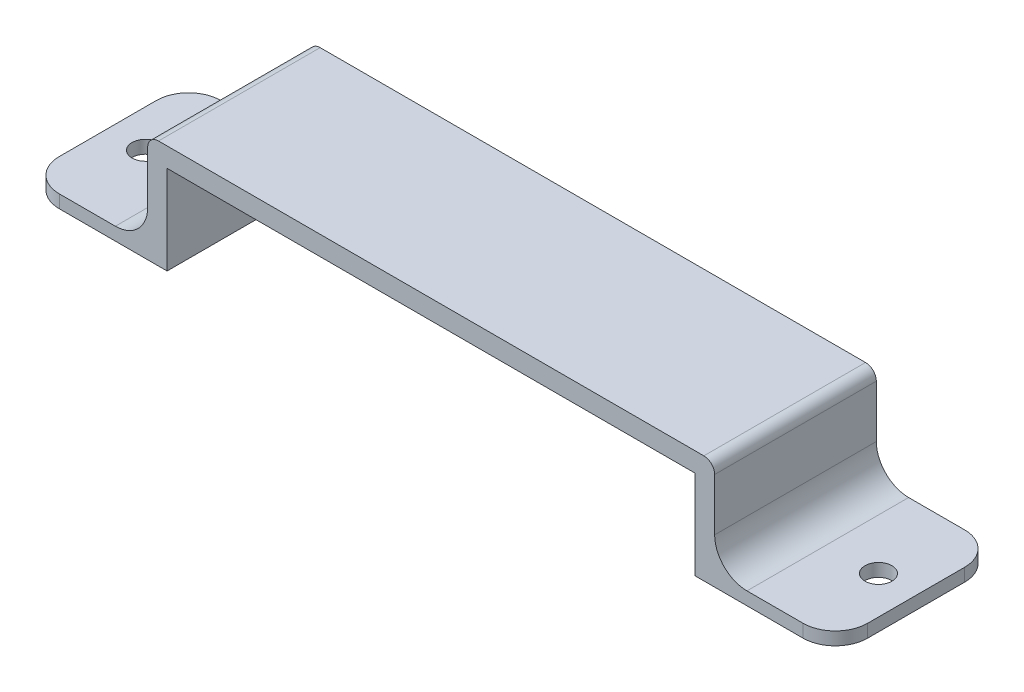
SolidWorks part; units mm, degrees
ref_plane "Front Plane" through (0, 0, 0) normal (0, 0, 1) x (1, 0, 0)
ref_plane "Top Plane" through (0, 0, 0) normal (0, 1, 0) x (1, 0, 0)
ref_plane "Right Plane" through (0, 0, 0) normal (1, 0, 0) x (0, 0, -1)
sketch "Sketch1" plane through (0, 0, 0) normal (0, 0, 1) x (1, 0, 0)
  line L0 (-21.8742, 0) -> (-8.8742, 0)
  line L1 (-8.8742, 0) -> (-8.8742, 8.25)
  line L2 (-8.8742, 8.25) -> (40.1258, 8.25)
  line L3 (40.1258, 8.25) -> (40.1258, 0)
  line L4 (40.1258, 0) -> (53.1258, 0)
  line L5 (53.1258, 0) -> (53.1258, 1.2)
  line L6 (53.1258, 1.2) -> (41.9258, 1.2)
  line L7 (41.9258, 1.2) -> (41.9258, 10.05)
  line L8 (41.9258, 10.05) -> (-10.6742, 10.05)
  line L9 (-10.6742, 10.05) -> (-10.6742, 1.2)
  line L10 (-10.6742, 1.2) -> (-21.8742, 1.2)
  line L11 (-21.8742, 1.2) -> (-21.8742, 0)
  point P12 (53.1258, 0.6)
  dimension "D1" = 1.2
  dimension "D2" = 75
  dimension "D3" = 49
  dimension "D4" = 1.8
  dimension "D5" = 8.25
  dimension "D6" = 1.8
extrude "Boss-Extrude1" add sketch "Sketch1" along normal blind 15
sketch "Sketch2" plane through (0, 1.2, 0) normal (0, 1, 0) x (1, 0, 0)
  line L1 (-21.8742, -7.5) -> (53.1258, -7.5) construction
  line L2 (-21.8742, -15) -> (-21.8742, 0) construction
  line L4 (53.1258, -15) -> (53.1258, 0) construction
  circle A0 centre (-18.3742, -7.5) radius 1.25
  circle A1 centre (49.6258, -7.5) radius 1.25
  point P10 (15.6258, -7.5)
  dimension "D1" = 2.5
  dimension "D2" = 2.5
  dimension "D3" = 68
  dimension "D4" = 34
extrude "Cut-Extrude1" cut sketch "Sketch2" against normal up to next
fillet "Fillet1" radius 3 6 edges at (53.1258, 0.6, 0) (53.1258, 0.6, 15) (41.9258, 1.2, 7.5) (-10.6742, 1.2, 7.5) (-21.8742, 0.6, 15) (-21.8742, 0.6, 0)
fillet "Fillet2" radius 1 2 edges at (-10.6742, 10.05, 7.5) (41.9258, 10.05, 7.5)
